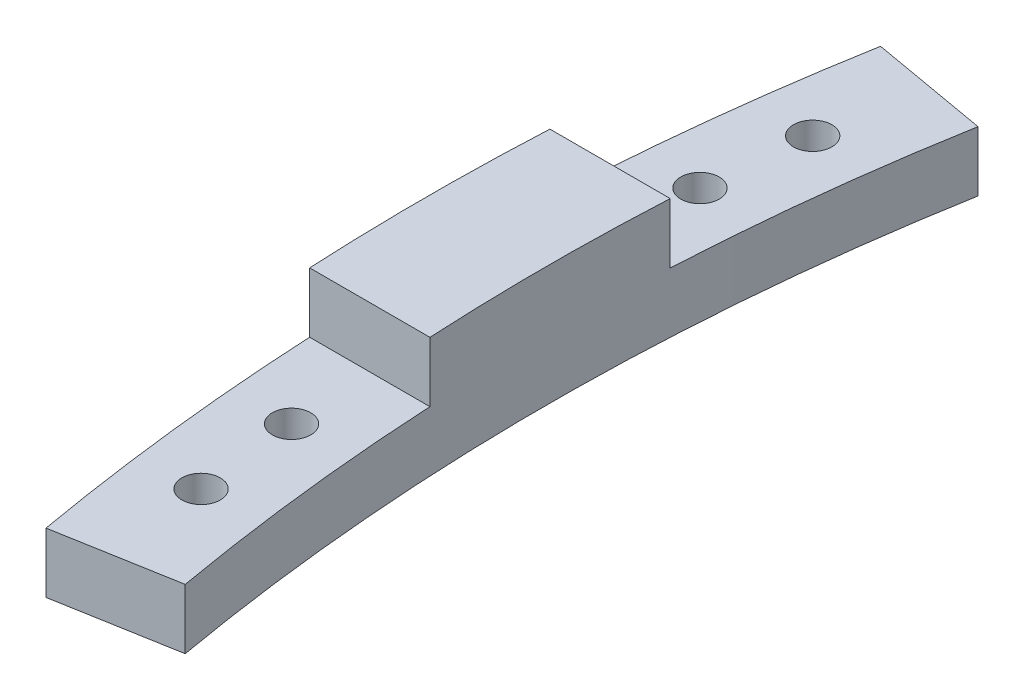
SolidWorks part; units mm, degrees
ref_plane "Front Plane" through (0, 0, 0) normal (0, 0, 1) x (1, 0, 0)
ref_plane "Top Plane" through (0, 0, 0) normal (0, 1, 0) x (1, 0, 0)
ref_plane "Right Plane" through (0, 0, 0) normal (1, 0, 0) x (0, 0, -1)
sketch "Sketch1" plane through (0, 0, 0) normal (0, 1, 0) x (1, 0, 0)
  line L0 (0, 0) -> (-196.9616, -34.7296) construction
  line L1 (0, 0) -> (-196.9616, 34.7296) construction
  line L2 (0, 0) -> (-195, 0) construction
  line L3 (-196.9616, 34.7296) -> (-187.1135, 32.9932)
  line L4 (-187.1135, -32.9932) -> (-196.9616, -34.7296)
  arc A0 (-196.9616, 34.7296) -> (-196.9616, -34.7296) centre (0, 0) ccw
  arc A1 (-187.1135, 32.9932) -> (-187.1135, -32.9932) centre (0, 0) ccw
  arc A2 (-192.0375, -33.8614) -> (-192.0375, 33.8614) centre (0, 0) cw construction
  point P8 (-196.0107, -34.7296)
  point P9 (0, 0)
  point P10 (-188.0079, -32.9932)
  point P11 (0, 0)
  dimension "D1" = 200
  dimension "D2" = 190
  dimension "D3" = 5
  dimension "D4" = 20
extrude "Boss-Extrude1" add sketch "Sketch1" along normal blind 5
sketch "Sketch2" [suppressed] plane through (0, 7.5, 0) normal (0, 1, 0) x (1, 0, 0)
  line L2 (0, 0) -> (-195, 0) construction
  line L3 (0, 0) -> (-199.4236, -35.1638) construction
  line L4 (0, 0) -> (-199.4236, 35.1638) construction
  line L5 (0, 0) -> (-190, 0) construction
  line L6 (0, 0) -> (-199.4236, -35.1638) construction
  line L7 (0, 0) -> (-199.4236, 35.1638) construction
  line L8 (0, 10) -> (-202.2529, 10) construction
  line L9 (0, 10) -> (0, -10) construction
  line L10 (0, -10) -> (-202.2529, -10) construction
  line L11 (-196.9616, 34.7296) -> (-187.1135, 32.9932)
  line L12 (-196.9616, -34.7296) -> (-187.1135, -32.9932)
  line L13 (-199.7498, -10) -> (-189.7367, -10)
  line L14 (-189.7367, 10) -> (-199.7498, 10)
  arc A0 (-196.9616, 34.7296) -> (-196.9616, -34.7296) centre (0, 0) ccw construction
  arc A1 (-187.1135, 32.9932) -> (-187.1135, -32.9932) centre (0, 0) ccw construction
  arc A2 (-196.9616, 34.7296) -> (-196.9616, -34.7296) centre (0, 0) ccw
  arc A3 (-187.1135, 32.9932) -> (-187.1135, -32.9932) centre (0, 0) ccw
  arc A4 (-199.4236, 35.1638) -> (-199.4236, -35.1638) centre (0, 0) ccw construction
  line M2 (-199.4236, -35.1638) -> (-184.6515, -32.559)
  line M4 (-184.6515, 32.559) -> (-199.4236, 35.1638)
  dimension "D1" = 20
extrude "Cut-Extrude1" [suppressed] cut sketch "Sketch2" against normal blind 1.5 contours A3 A2 L14 M4 | A3 L13 A2 M2
ref_plane "Plane1" through (-195, 0, 0) normal (1, 0, 0) x (0, 0, -1)
sketch "Sketch6" [suppressed] plane through (0, 0, 0) normal (0, -1, 0) x (1, 0, 0)
  line L0 (0, 0) -> (-194.258, 16.9954) construction
  line L1 (0, 0) -> (-195, 0) construction
  line L2 (0, 0) -> (-195, 0) construction
  line L3 (0, 0) -> (-194.258, -16.9954) construction
  arc A0 (-192.0375, 33.8614) -> (-192.0375, -33.8614) centre (0, 0) ccw construction
  dimension "D1" = 5
hole_wizard "Ø3.1 (3.1) Diameter Hole1" [suppressed] positions "Sketch7" profile "Sketch8" hole size "Ø3.1" standard "ISO"
sketch "Sketch7" [suppressed] plane through (0, 0, 0) normal (0, -1, 0) x (-1, 0, 0)
  point P0 (194.258, -16.9954)
  point P3 (194.258, 16.9954)
sketch "Sketch8" plane through (-194.258, 0, 16.9954) normal (1, 0, 0) x (0, 0, -1)
  line L0 (0, 0) -> (0, 7.5)
  line L1 (0, 7.5) -> (1.55, 7.5)
  line L2 (1.55, 7.5) -> (1.55, 0)
  line L5 (1.55, 0) -> (0, 0)
  line L11 (0, -6.35) -> (0, 107.95) construction
  dimension "Thru Hole Dia." = 3.1
  dimension "Thru Hole Depth" = 7.5
sketch "Sketch9" plane through (0, 5, 0) normal (0, 1, 0) x (1, 0, 0)
  line L0 (0, 10) -> (0, -10) construction
  line L1 (0, 0) -> (-200, 0) construction
  line L2 (-199.7498, 10) -> (-189.7367, 10)
  line L3 (-199.7498, -10) -> (-189.7367, -10)
  arc A0 (-196.9616, 34.7296) -> (-196.9616, -34.7296) centre (0, 0) ccw construction
  arc A1 (-187.1135, 32.9932) -> (-187.1135, -32.9932) centre (0, 0) ccw construction
  arc A2 (-189.7367, 10) -> (-189.7367, -10) centre (0, 0) ccw
  arc A3 (-199.7498, 10) -> (-199.7498, -10) centre (0, 0) ccw
  point P1 (0, 11.4379)
  point P12 (-200, -12.9251)
  point P18 (0, -11.5204)
  dimension "D1" = 20
extrude "Boss-Extrude2" add sketch "Sketch9" along normal blind 5
ref_plane "Plane2" through (-195, 0, 0) normal (-1, 0, 0) x (0, 0, 1)
sketch "Sketch10" plane through (-195, 0, 0) normal (-1, 0, 0) x (0, 0, 1)
  line L0 (10, 10) -> (-10, 10) construction
  line L1 (3.5, 13.5) -> (-3.5, 13.5)
  line L2 (3.5, 13.5) -> (3.5, 6.5)
  line L3 (3.5, 6.5) -> (-3.5, 6.5)
  line L4 (-3.5, 13.5) -> (-3.5, 6.5)
  line L5 (3.5, 13.5) -> (-3.5, 6.5) construction
  line L6 (3.5, 6.5) -> (-3.5, 13.5) construction
  point P0 (0, 10)
  dimension "D1" = 7
  dimension "D2" = 7
sketch "Sketch11" plane through (-195, 0, 0) normal (-1, 0, 0) x (0, 0, 1)
  line L0 (10, 10) -> (-10, 10) construction
  circle A0 centre (0, 10) radius 2.1
  dimension "D1" = 4.2
sketch "Sketch12" plane through (0, 5, 0) normal (0, 1, 0) x (1, 0, 0)
  line L0 (0, 0) -> (-194.258, -16.9954) construction
  line L1 (0, 0) -> (-193.3317, -25.4526) construction
  line L2 (0, 0) -> (-195, 0) construction
  line L3 (0, 0) -> (-195, 0) construction
  line L4 (0, 0) -> (-194.258, 16.9954) construction
  line L5 (0, 0) -> (-193.3317, 25.4526) construction
  arc A0 (-192.0375, 33.8614) -> (-192.0375, -33.8614) centre (0, 0) ccw construction
  dimension "D1" = 10
  dimension "D2" = 15
hole_wizard "Ø3.2 (3.2) Diameter Hole1" positions "Sketch13" profile "Sketch14" hole size "Ø3.2" standard "ISO" end condition through all
sketch "Sketch13" plane through (0, 5, 0) normal (0, 1, 0) x (1, 0, 0)
  point P0 (-194.258, 16.9954)
  point P3 (-193.3317, 25.4526)
  point P6 (-194.258, -16.9954)
  point P9 (-193.3317, -25.4526)
sketch "Sketch14" plane through (-194.258, 5, -16.9954) normal (1, 0, 0) x (0, 0, 1)
  line L0 (0, 0) -> (0, 5)
  line L1 (0, 5) -> (1.6, 5)
  line L2 (1.6, 5) -> (1.6, 0)
  line L5 (1.6, 0) -> (0, 0)
  line L11 (0, -6.35) -> (0, 107.95) construction
  dimension "Thru Hole Dia." = 3.2
  dimension "Thru Hole Depth" = 5
